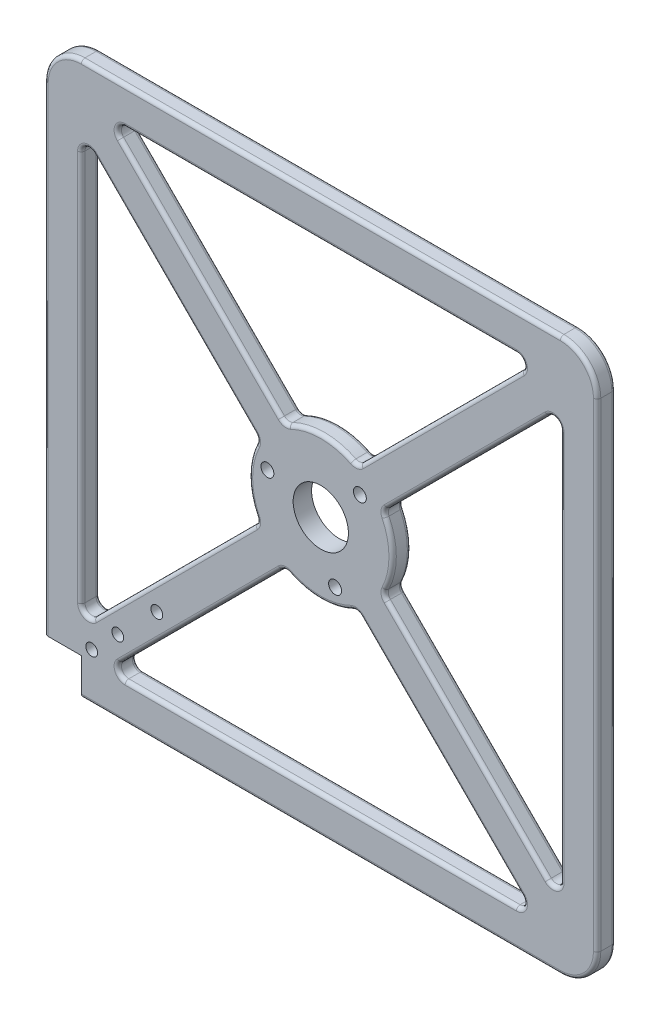
SolidWorks part; units mm, degrees
ref_plane "Front Plane" through (0, 0, 0) normal (0, 0, 1) x (1, 0, 0)
ref_plane "Top Plane" through (0, 0, 0) normal (0, 1, 0) x (1, 0, 0)
ref_plane "Right Plane" through (0, 0, 0) normal (1, 0, 0) x (0, 0, -1)
sketch "Sketch1" plane through (0, 0, 0) normal (0, 0, 1) x (1, 0, 0)
  line L0 (-65, -53.1005) -> (-65, 53.1005)
  line L1 (75, -75) -> (-75, -75) construction
  line L2 (75, -75) -> (75, 75) construction
  line L3 (75, 75) -> (-75, 75) construction
  line L4 (-75, -75) -> (-75, 75) construction
  line L5 (75, -75) -> (-75, 75) construction
  line L6 (75, 75) -> (-75, -75) construction
  line L7 (53.1005, 65) -> (-53.1005, 65)
  line L8 (65, -53.1005) -> (65, 53.1005)
  line L9 (53.1005, -65) -> (-53.1005, -65)
  line L10 (61.5858, -54.5147) -> (17.91, -10.8389)
  line L11 (78.5355, 71.4645) -> (-71.4645, -78.5355) construction
  line L12 (54.5147, -61.5858) -> (10.8389, -17.91)
  line L13 (61.5858, 54.5147) -> (17.91, 10.8389)
  line L14 (71.4645, -78.5355) -> (-78.5355, 71.4645) construction
  line L15 (54.5147, 61.5858) -> (10.8389, 17.91)
  line L16 (78.5355, -71.4645) -> (-71.4645, 78.5355) construction
  line L17 (-17.91, -10.8389) -> (-61.5858, -54.5147)
  line L18 (-10.8389, 17.91) -> (-54.5147, 61.5858)
  line L19 (-17.91, 10.8389) -> (-61.5858, 54.5147)
  line L20 (-65, -65) -> (-65, 65) construction
  line L21 (-10.8389, -17.91) -> (-54.5147, -61.5858)
  line L22 (65, -65) -> (-65, -65) construction
  line L23 (65, -65) -> (65, 65) construction
  line L24 (65, 65) -> (-65, 65) construction
  line L25 (-75, -65) -> (-65, -65)
  line L30 (-65, -65) -> (-65, -75)
  line L31 (-65, -75) -> (65, -75)
  line L32 (65, -75) -> (65, -65)
  line L33 (65, -65) -> (75, -65)
  line L34 (75, -65) -> (75, 65)
  line L35 (75, 65) -> (65, 65)
  line L36 (65, 65) -> (65, 75)
  line L37 (65, 75) -> (-65, 75)
  line L38 (-65, 75) -> (-65, 65)
  line L39 (-65, 65) -> (-75, 65)
  line L40 (-75, 65) -> (-75, -65)
  circle A6 centre (0, 0) radius 7.5
  arc A7 (-8.548, -17.5266) -> (8.548, -17.5266) centre (0, 0) ccw
  arc A8 (-16.8631, -9.7921) -> (-13.7886, -13.7886) centre (0, 0) ccw construction
  circle A9 centre (0, 0) radius 19.5 construction
  arc A10 (-13.7886, -13.7886) -> (-9.7921, -16.8631) centre (0, 0) ccw construction
  arc A11 (9.7921, -16.8631) -> (13.7886, -13.7886) centre (0, 0) ccw construction
  arc A12 (17.5266, -8.548) -> (17.5266, 8.548) centre (0, 0) ccw
  arc A13 (13.7886, -13.7886) -> (16.8631, -9.7921) centre (0, 0) ccw construction
  arc A14 (16.8631, 9.7921) -> (13.7886, 13.7886) centre (0, 0) ccw construction
  arc A15 (8.548, 17.5266) -> (-8.548, 17.5266) centre (0, 0) ccw
  arc A16 (13.7886, 13.7886) -> (9.7921, 16.8631) centre (0, 0) ccw construction
  arc A17 (-9.7921, 16.8631) -> (-13.7886, 13.7886) centre (0, 0) ccw construction
  arc A18 (-17.5266, 8.548) -> (-17.5266, -8.548) centre (0, 0) ccw
  arc A19 (-13.7886, 13.7886) -> (-16.8631, 9.7921) centre (0, 0) ccw construction
  arc A20 (10.8389, 17.91) -> (8.548, 17.5266) centre (9.4247, 19.3242) cw
  arc A21 (-10.8389, 17.91) -> (-8.548, 17.5266) centre (-9.4247, 19.3242) ccw
  arc A22 (-53.1005, 65) -> (-54.5147, 61.5858) centre (-53.1005, 63) ccw
  arc A23 (54.5147, 61.5858) -> (53.1005, 65) centre (53.1005, 63) ccw
  arc A24 (61.5858, -54.5147) -> (65, -53.1005) centre (63, -53.1005) ccw
  arc A25 (61.5858, 54.5147) -> (65, 53.1005) centre (63, 53.1005) cw
  arc A26 (17.91, 10.8389) -> (17.5266, 8.548) centre (19.3242, 9.4247) ccw
  arc A27 (17.91, -10.8389) -> (17.5266, -8.548) centre (19.3242, -9.4247) cw
  arc A28 (-10.8389, -17.91) -> (-8.548, -17.5266) centre (-9.4247, -19.3242) cw
  arc A29 (10.8389, -17.91) -> (8.548, -17.5266) centre (9.4247, -19.3242) ccw
  arc A30 (54.5147, -61.5858) -> (53.1005, -65) centre (53.1005, -63) cw
  arc A31 (-54.5147, -61.5858) -> (-53.1005, -65) centre (-53.1005, -63) ccw
  arc A32 (-65, -53.1005) -> (-61.5858, -54.5147) centre (-63, -53.1005) ccw
  arc A33 (-17.91, -10.8389) -> (-17.5266, -8.548) centre (-19.3242, -9.4247) ccw
  arc A34 (-17.91, 10.8389) -> (-17.5266, 8.548) centre (-19.3242, 9.4247) cw
  arc A35 (-65, 53.1005) -> (-61.5858, 54.5147) centre (-63, 53.1005) cw
  point P0 (0, 0)
  point P92 (-75, 0)
  point P93 (75, 0)
  point P94 (0, 75)
  point P95 (0, -75)
  dimension "D3" = 15
  dimension "D9" = 2
  dimension "D1" = 150
  dimension "D7" = 5
  dimension "D8" = 5
  dimension "D10" = 10
  dimension "D2" = 10
  dimension "D4" = 12
  dimension "D5" = 5
  dimension "D6" = 5
extrude "Boss-Extrude1" add sketch "Sketch1" along normal mid plane 5
fillet "Fillet1" radius 1 64 edges at (-17.3516, -9.7548, 2.5) (-39.7479, -32.6768, 2.5) (-63.7654, -54.9483, 2.5) (-65, 0, 2.5) (-63.7654, 54.9483, 2.5) (-39.7479, 32.6768, 2.5) (-17.3516, 9.7548, 2.5) (-17.3516, -9.7548, -2.5) (-39.7479, -32.6768, -2.5) (-63.7654, -54.9483, -2.5) (-65, 0, -2.5) (-63.7654, 54.9483, -2.5) (-39.7479, 32.6768, -2.5) (-17.3516, 9.7548, -2.5) (0, -65, 2.5) (-54.9483, -63.7654, 2.5) (-32.6768, -39.7479, 2.5) (-9.7548, -17.3516, 2.5) (0, -19.5, 2.5) (9.7548, -17.3516, 2.5) (32.6768, -39.7479, 2.5) (0, -65, -2.5) (-54.9483, -63.7654, -2.5) (-32.6768, -39.7479, -2.5) (-9.7548, -17.3516, -2.5) (0, -19.5, -2.5) (9.7548, -17.3516, -2.5) (32.6768, -39.7479, -2.5) (63.7654, -54.9483, 2.5) (39.7479, -32.6768, 2.5) (17.3516, -9.7548, 2.5) (19.5, 0, 2.5) (17.3516, 9.7548, 2.5) (39.7479, 32.6768, 2.5) (63.7654, 54.9483, 2.5) (63.7654, -54.9483, -2.5) (39.7479, -32.6768, -2.5) (17.3516, -9.7548, -2.5) (19.5, 0, -2.5) (17.3516, 9.7548, -2.5) (39.7479, 32.6768, -2.5) (63.7654, 54.9483, -2.5) (9.7548, 17.3516, 2.5) (0, 19.5, 2.5) (-9.7548, 17.3516, 2.5) (-32.6768, 39.7479, 2.5) (-54.9483, 63.7654, 2.5) (0, 65, 2.5) (54.9483, 63.7654, 2.5) (9.7548, 17.3516, -2.5) (0, 19.5, -2.5) (-9.7548, 17.3516, -2.5) (-32.6768, 39.7479, -2.5) (-54.9483, 63.7654, -2.5) (0, 65, -2.5) (54.9483, 63.7654, -2.5) (-19.5, 0, 2.5) (-19.5, 0, -2.5) (54.9483, -63.7654, 2.5) (54.9483, -63.7654, -2.5) (65, 0, 2.5) (65, 0, -2.5) (32.6768, 39.7479, 2.5) (32.6768, 39.7479, -2.5)
sketch "Sketch3" plane through (0, 0, -2.5) normal (0, 0, -1) x (-1, 0, 0)
  line L0 (0, 0) -> (0, -87.9239) construction
  line L2 (62.1716, -62.1716) -> (0, 0) construction
  circle A0 centre (44.4939, -44.4939) radius 1.6
  circle A1 centre (62.1716, -62.1716) radius 1.6
  circle A2 centre (0, 0) radius 87.9239 construction
  circle A6 centre (55.1005, -55.1005) radius 1.6
  point P15 (0, 0)
  dimension "D1" = 175.8478
  dimension "D2" = 3.2
  dimension "D3" = 45
  dimension "D4" = 25
  dimension "D5" = 15
sketch "Sketch5" plane through (0, 0, 2.5) normal (0, 0, 1) x (1, 0, 0)
  line L0 (0, 0) -> (10.6066, 10.6066) construction
  line L1 (17.2029, 11.546) -> (60.8787, 55.2218) construction
  circle A0 centre (0, 0) radius 15 construction
  circle A1 centre (10.6066, 10.6066) radius 1.75
  circle A2 centre (3.8823, -14.4889) radius 1.75
  circle A3 centre (-14.4889, 3.8823) radius 1.75
  point P13 (0, 0)
  dimension "D1" = 30
  dimension "D2" = 3.5
  dimension "D3" = 3
extrude "Cut-Extrude3" cut sketch "Sketch5" against normal through all both and the other way through all
sketch "Sketch6" plane through (0, 65, 0) normal (0, 1, 0) x (1, 0, 0)
  line L4 (75, 2.5) -> (65, 2.5)
  line L5 (65, 2.5) -> (65, -2.5)
  line L6 (65, -2.5) -> (75, -2.5)
  line L7 (75, -2.5) -> (75, 2.5)
  line L8 (75, 2.5) -> (65, 2.5)
  line L9 (65, 2.5) -> (65, -2.5)
  line L10 (65, -2.5) -> (75, -2.5)
  line L11 (75, -2.5) -> (75, 2.5)
  line L12 (-65, 2.5) -> (-75, 2.5)
  line L13 (-75, 2.5) -> (-75, -2.5)
  line L14 (-75, -2.5) -> (-65, -2.5)
  line L15 (-65, -2.5) -> (-65, 2.5)
  line L16 (-65, 2.5) -> (-75, 2.5)
  line L17 (-75, 2.5) -> (-75, -2.5)
  line L18 (-75, -2.5) -> (-65, -2.5)
  line L19 (-65, -2.5) -> (-65, 2.5)
  dimension "D1" = 0
  dimension "D2" = 0
extrude "Boss-Extrude4" add sketch "Sketch6" along normal up to surface (10 mm away) up to face at (0, 75, 0)
sketch "Sketch7" plane through (65, 0, 0) normal (1, 0, 0) x (0, 0, -1)
  line L4 (2.5, -75) -> (2.5, -65)
  line L5 (2.5, -65) -> (-2.5, -65)
  line L6 (-2.5, -65) -> (-2.5, -75)
  line L7 (-2.5, -75) -> (2.5, -75)
  line L8 (2.5, -75) -> (2.5, -65)
  line L9 (2.5, -65) -> (-2.5, -65)
  line L10 (-2.5, -65) -> (-2.5, -75)
  line L11 (-2.5, -75) -> (2.5, -75)
  dimension "D1" = 0
extrude "Boss-Extrude5" add sketch "Sketch7" along normal up to surface (10 mm away) up to face at (75, 5, 0)
fillet "Fillet2" radius 10 3 edges at (-75, 75, 0) (75, -75, 0) (75, 75, 0)
extrude "Cut-Extrude4" cut sketch "Sketch3" against normal through all both
fillet "Fillet3" radius 1 14 edges at (0, -75, -2.5) (0, -75, 2.5) (72.0711, -72.0711, -2.5) (72.0711, -72.0711, 2.5) (75, 0, 2.5) (75, 0, -2.5) (72.0711, 72.0711, -2.5) (72.0711, 72.0711, 2.5) (0, 75, -2.5) (0, 75, 2.5) (-75, 0, 2.5) (-75, 0, -2.5) (-72.0711, 72.0711, 2.5) (-72.0711, 72.0711, -2.5)
equation "\"D6@Sketch1\"=\"D7@Sketch1\""
equation "\"D8@Sketch1\"=\"D7@Sketch1\""
equation "\"D5@Sketch1\"=\"D7@Sketch1\""
